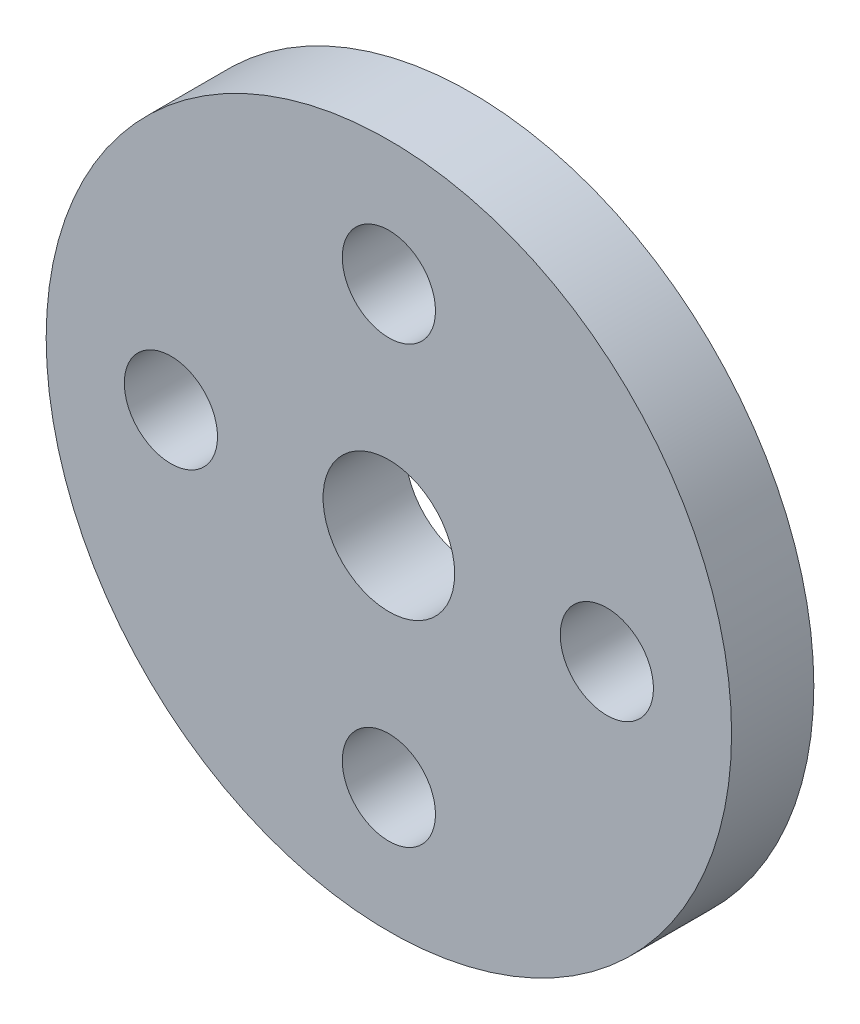
SolidWorks part; units mm, degrees
ref_plane "前基準面" through (0, 0, 0) normal (0, 0, 1) x (1, 0, 0)
ref_plane "上基準面" through (0, 0, 0) normal (0, 1, 0) x (1, 0, 0)
ref_plane "右基準面" through (0, 0, 0) normal (1, 0, 0) x (0, 0, -1)
sketch "草圖1" plane through (0, 0, 0) normal (0, 0, 1) x (1, 0, 0)
  line L0 (0, 0) -> (0, 7.95) construction
  line L1 (0, 0) -> (7.95, 0) construction
  line L2 (0, 0) -> (-7.95, 0) construction
  line L3 (7.95, 0) -> (0, 7.95) construction
  line L4 (0, 7.95) -> (-7.95, 0) construction
  line L5 (-7.95, 0) -> (0, -7.95) construction
  line L6 (0, -7.95) -> (7.95, 0) construction
  circle A0 centre (0, 0) radius 2.4
  circle A1 centre (0, 7.95) radius 1.7
  circle A2 centre (7.95, 0) radius 1.7
  circle A3 centre (0, -7.95) radius 1.7
  circle A4 centre (-7.95, 0) radius 1.7
  circle A5 centre (0, 0) radius 12.5
  dimension "D1" = 4.8
  dimension "D2" = 3.4
  dimension "D4" = 25
  dimension "D3" = 11.243
extrude "伸長1" add sketch "草圖1" along normal blind 3
